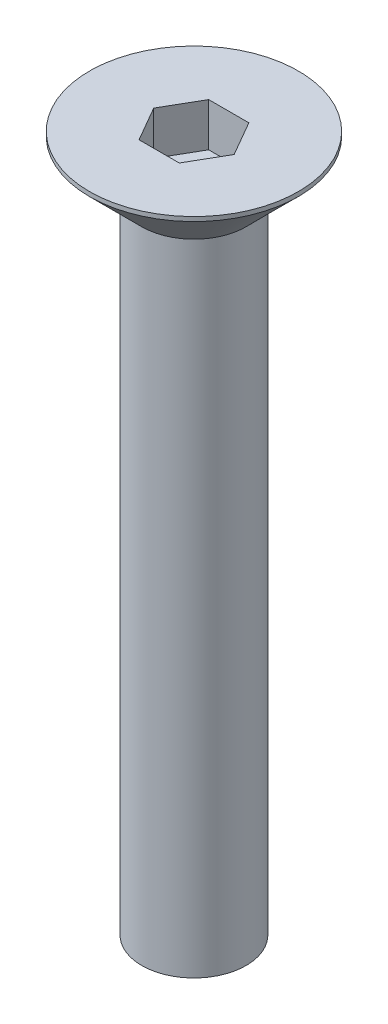
SolidWorks part; units mm, degrees
material "AISI 304"
ref_plane "Front Plane" through (0, 0, 0) normal (0, 0, 1) x (1, 0, 0)
ref_plane "Top Plane" through (0, 0, 0) normal (0, 1, 0) x (1, 0, 0)
ref_plane "Right Plane" through (0, 0, 0) normal (1, 0, 0) x (0, 0, -1)
sketch "Sketch1" plane through (0, 0, 0) normal (0, 0, 1) x (1, 0, 0)
  line L0 (0, 61.6916) -> (0, -59.3578) construction
  line L1 (0, -80) -> (6, -80)
  line L2 (6, -80) -> (6, -6.5)
  line L3 (-7.9826, -4.5174) -> (-6, -6.5) construction
  line L4 (12, -0.5) -> (12, 0)
  line L5 (12, 0) -> (0, 0)
  line L6 (0, 0) -> (0, -80)
  line L7 (6, -6.5) -> (12, -0.5)
  dimension "D1" = 90
  dimension "D2" = 24
  dimension "D3" = 12
  dimension "D4" = 0.5
  dimension "D5" = 80
revolve "Revolve1" add sketch "Sketch1" angle 360 about L0
sketch "Sketch2" plane through (0, 0, 0) normal (0, 1, 0) x (-1, 0, 0)
  line L1 (-2.3094, -4) -> (2.3094, -4)
  line L2 (2.3094, -4) -> (4.6188, 0)
  line L3 (4.6188, 0) -> (2.3094, 4)
  line L4 (2.3094, 4) -> (-2.3094, 4)
  line L5 (-2.3094, 4) -> (-4.6188, 0)
  line L6 (-4.6188, 0) -> (-2.3094, -4)
  circle A0 centre (0, 0) radius 4 construction
  dimension "D1" = 8
extrude "Cut-Extrude1" cut sketch "Sketch2" against normal blind 5
